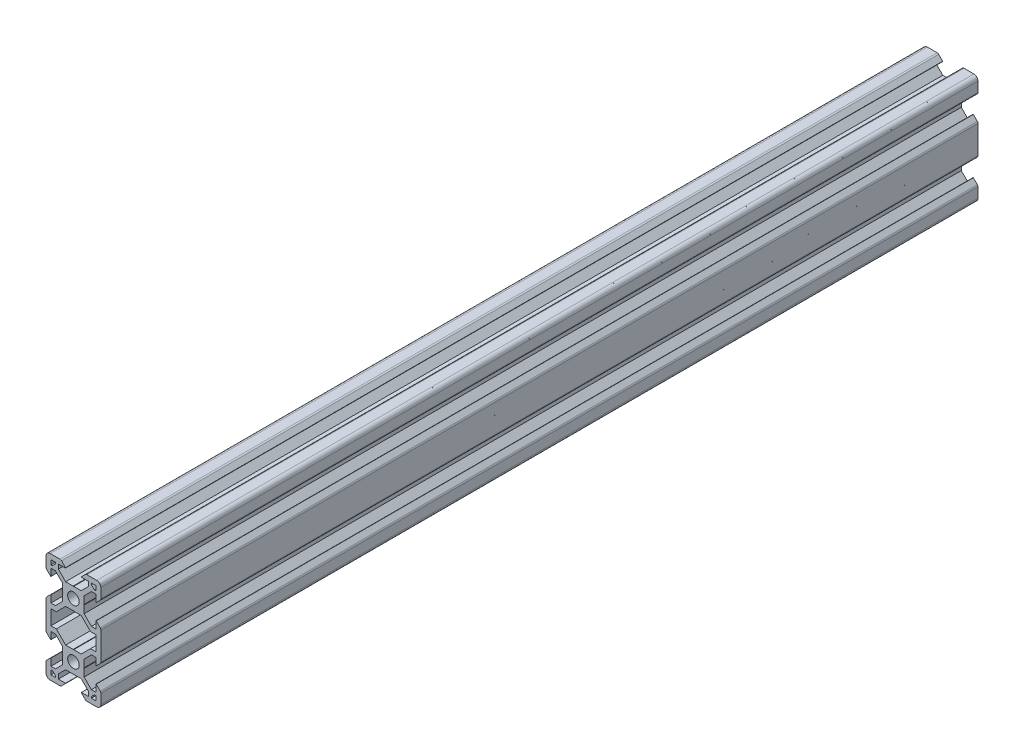
SolidWorks part; units mm, degrees
ref_plane "Front Plane" through (0, 0, 0) normal (0, 0, 1) x (1, 0, 0)
ref_plane "Top Plane" through (0, 0, 0) normal (0, 1, 0) x (1, 0, 0)
ref_plane "Right Plane" through (0, 0, 0) normal (1, 0, 0) x (0, 0, -1)
sketch "Sketch1" plane through (0, 0, 0) normal (0, 0, 1) x (1, 0, 0)
  line L0 (-8.2, 2.8875) -> (-8.2, 5.4975)
  line L3 (-4.9072, 9.9975) -> (-8.5, 9.9975)
  line L4 (-10, 4.9047) -> (-10, 8.4975)
  line L5 (-2.1, 0) -> (-3.8, 0) construction
  line L6 (0, 3.8) -> (0, 0) construction
  line L7 (-0.1, 3.9) -> (-2.8404, 3.9)
  line L8 (-3.9, 0.1) -> (-3.9, 2.8383)
  line L9 (-2.89, 8.1975) -> (-5.5, 8.1975)
  line L10 (-6.57, 8.1975) -> (-6.57, 7.6575)
  line L11 (-8.2, 6.5675) -> (-7.66, 6.5675)
  line L12 (-5.5, 8.1975) -> (-5.5, 6.5588)
  line L13 (-6.56, 5.4975) -> (-8.2, 5.4975)
  line L14 (-8.2, 8.1975) -> (-1.4852, 1.4847) construction
  line L15 (-6.56, 5.4975) -> (-3.9, 2.8383)
  line L16 (-5.5, 6.5588) -> (-2.8404, 3.9)
  line L17 (-7.66, 6.5675) -> (-6.57, 7.6575)
  line L18 (-8.7302, 7.6671) -> (-0.5302, -0.5304) construction
  line L19 (-7.6698, 8.7279) -> (0.5302, 0.5304) construction
  line L20 (-8.2, 8.1975) -> (0, 0) construction
  line L21 (-8.2, 6.5675) -> (-8.2, 8.1975)
  line L22 (-8.2, -0.0025) -> (-8.2, 8.1975) construction
  line L23 (-6.57, 8.1975) -> (-8.2, 8.1975)
  line L24 (0, 8.1975) -> (-8.2, 8.1975) construction
  line L25 (-10, -0.0025) -> (-10, 9.9975) construction
  line L26 (0, 9.9975) -> (-10, 9.9975) construction
  line L27 (-2.89, 8.3075) -> (-2.89, 8.1975)
  line L29 (-8.31, 2.8875) -> (-8.2, 2.8875)
  line L30 (-4.3486, 9.7661) -> (-2.89, 8.3075)
  line L31 (-8.31, 2.8875) -> (-9.7686, 4.3461)
  line L34 (-0.1, 3.9) -> (0, 3.8)
  line L35 (-3.9, 0.1) -> (-3.8, 0)
  line L36 (-8.2, -7.2996) -> (-6.24, -7.2996)
  line L37 (0, 0) -> (0, -10) construction
  line L38 (-0.1, -3.9) -> (-2.8404, -3.9)
  line L39 (-3.8, 0) -> (-3.9, -0.1)
  line L40 (-3.9, -0.1) -> (-3.9, -2.84)
  line L41 (-2.8404, -3.9) -> (-6.24, -7.2996)
  line L42 (-3.9, -2.84) -> (-6.56, -5.5)
  line L43 (-8.2, -2.89) -> (-8.2, -5.5)
  line L44 (-6.56, 5.4975) -> (-6.56, -5.5) construction
  line L45 (-6.56, -5.5) -> (-8.2, -5.5)
  line L46 (-0.1, -3.9) -> (0, -3.8)
  line L48 (-8.2, -2.89) -> (-8.31, -2.89)
  line L49 (-8.31, -2.89) -> (-9.7657, -4.3457)
  line L52 (-10, -10) -> (0, -10) construction
  line L53 (-8.2, -7.2996) -> (-8.2, -10)
  line L61 (-10, -4.9114) -> (-10, -10)
  arc A1 (-10, 8.4975) -> (-8.5, 9.9975) centre (-8.5, 8.4975) cw
  arc A2 (-9.7686, 4.3461) -> (-10, 4.9047) centre (-9.21, 4.9047) cw
  arc A3 (-4.3486, 9.7661) -> (-4.9072, 9.9975) centre (-4.9072, 9.2075) ccw
  arc A4 (-9.7657, -4.3457) -> (-10, -4.9114) centre (-9.2, -4.9114) ccw
  arc A6 (0, 2.1) -> (0, -2.1) centre (0, 0) ccw
  point P29 (-10, 9.9975)
  point P39 (-10, 4.5775)
  point P42 (-4.58, 9.9975)
  point P48 (-10, -4.58)
  dimension "D15" = 1.5
  dimension "D22" = 0.79
  dimension "D30" = 1.96
  dimension "D31" = 2.1
  dimension "D39" = 0.8
  dimension "D4" = 1.8
  dimension "D5" = 3.43
  dimension "D6" = 3.43
  dimension "D7" = 0.54
  dimension "D8" = 0.54
  dimension "D9" = 1.07
  dimension "D10" = 1.07
  dimension "D11" = 3.9
  dimension "D12" = 3.9
  dimension "D16" = 7.11
  dimension "D17" = 0.11
  dimension "D18" = 1.69
  dimension "D19" = 0.11
  dimension "D20" = 7.11
  dimension "D21" = 1.69
  dimension "D23" = 10
  dimension "D24" = 0.1
  dimension "D25" = 45
  dimension "D26" = 0.1
  dimension "D27" = 45
  dimension "D28" = 1.64
  dimension "D29" = 10
  dimension "D32" = 3.9
  dimension "D33" = 45
  dimension "D34" = 2.74
  dimension "D35" = 45
  dimension "D37" = 2.61
  dimension "D38" = 90
  dimension "D40" = 0.1
  dimension "D41" = 45
  dimension "D13" = 0.75
  dimension "D14" = 0.75
sketch "Sketch2" plane through (0, 0, 0) normal (0, 0, 1) x (1, 0, 0)
  line L0 (-0.1, 3.9) -> (0, 3.8) construction
  line L1 (-0.1, 3.9) -> (-2.8404, 3.9) construction
  line L2 (-5.5, 6.5588) -> (-2.8404, 3.9) construction
  line L3 (-5.5, 8.1975) -> (-5.5, 6.5588) construction
  line L4 (-2.89, 8.1975) -> (-5.5, 8.1975) construction
  line L5 (-7.66, 6.5675) -> (-6.57, 7.6575)
  line L6 (-6.57, 7.6575) -> (-6.57, 8.1975)
  line L7 (-6.57, 8.1975) -> (-8.2, 8.1975)
  line L8 (-8.2, 8.1975) -> (-8.2, 6.5675)
  line L9 (-8.2, 6.5675) -> (-7.66, 6.5675)
  line L10 (-7.66, 6.5675) -> (-6.57, 7.6575)
  line L11 (-6.57, 7.6575) -> (-6.57, 8.1975)
  line L12 (-6.57, 8.1975) -> (-8.2, 8.1975)
  line L13 (-8.2, 8.1975) -> (-8.2, 6.5675)
  line L14 (-8.2, 6.5675) -> (-7.66, 6.5675)
  line L15 (-2.89, 8.3075) -> (-2.89, 8.1975) construction
  line L16 (-4.3486, 9.7661) -> (-2.89, 8.3075) construction
  line L17 (-4.9072, 9.9975) -> (-8.5, 9.9975) construction
  line L18 (-10, 4.9047) -> (-10, 8.4975) construction
  line L19 (-8.31, 2.8875) -> (-9.7686, 4.3461) construction
  line L20 (-8.31, 2.8875) -> (-8.2, 2.8875) construction
  line L21 (-8.2, 2.8875) -> (-8.2, 5.4975) construction
  line L22 (-6.56, 5.4975) -> (-8.2, 5.4975) construction
  line L23 (-6.56, 5.4975) -> (-3.9, 2.8383) construction
  line L24 (-3.9, 0.1) -> (-3.9, 2.8383) construction
  line L25 (-3.9, 0.1) -> (-3.8, 0) construction
  line L26 (-3.8, 0) -> (-3.9, -0.1) construction
  line L27 (-3.9, -0.1) -> (-3.9, -2.84) construction
  line L28 (-3.9, -2.84) -> (-6.56, -5.5) construction
  line L29 (-6.56, -5.5) -> (-8.2, -5.5) construction
  line L30 (-8.2, -2.89) -> (-8.2, -5.5) construction
  line L31 (-8.2, -2.89) -> (-8.31, -2.89) construction
  line L32 (-8.31, -2.89) -> (-9.7657, -4.3457) construction
  line L33 (-10, -4.9114) -> (-10, -10) construction
  line L34 (-0.1, -3.9) -> (0, -3.8) construction
  line L35 (-0.1, -3.9) -> (-2.8404, -3.9) construction
  line L36 (-2.8404, -3.9) -> (-6.24, -7.2996) construction
  line L37 (-8.2, -7.2996) -> (-6.24, -7.2996) construction
  line L38 (-8.2, -7.2996) -> (-8.2, -10) construction
  line L39 (-0.1, 3.9) -> (0, 3.8)
  line L40 (-0.1, 3.9) -> (-2.8404, 3.9)
  line L41 (-5.5, 6.5588) -> (-2.8404, 3.9)
  line L42 (-5.5, 8.1975) -> (-5.5, 6.5588)
  line L43 (-2.89, 8.1975) -> (-5.5, 8.1975)
  line L44 (-2.89, 8.3075) -> (-2.89, 8.1975)
  line L45 (-4.3486, 9.7661) -> (-2.89, 8.3075)
  line L46 (-4.9072, 9.9975) -> (-8.5, 9.9975)
  line L47 (-10, 4.9047) -> (-10, 8.4975)
  line L48 (-8.31, 2.8875) -> (-9.7686, 4.3461)
  line L49 (-8.31, 2.8875) -> (-8.2, 2.8875)
  line L50 (-8.2, 2.8875) -> (-8.2, 5.4975)
  line L51 (-6.56, 5.4975) -> (-8.2, 5.4975)
  line L52 (-6.56, 5.4975) -> (-3.9, 2.8383)
  line L53 (-3.9, 0.1) -> (-3.9, 2.8383)
  line L54 (-3.9, 0.1) -> (-3.8, 0)
  line L55 (-3.8, 0) -> (-3.9, -0.1)
  line L56 (-3.9, -0.1) -> (-3.9, -2.84)
  line L57 (-3.9, -2.84) -> (-6.56, -5.5)
  line L58 (-6.56, -5.5) -> (-8.2, -5.5)
  line L59 (-8.2, -2.89) -> (-8.2, -5.5)
  line L60 (-8.2, -2.89) -> (-8.31, -2.89)
  line L61 (-8.31, -2.89) -> (-9.7657, -4.3457)
  line L62 (-10, -4.9114) -> (-10, -15.0886)
  line L63 (-0.1, -3.9) -> (0, -3.8)
  line L64 (-0.1, -3.9) -> (-2.8404, -3.9)
  line L65 (-2.8404, -3.9) -> (-6.24, -7.2996)
  line L66 (-8.2, -7.2996) -> (-6.24, -7.2996)
  line L67 (-8.2, -7.2996) -> (-8.2, -12.7004)
  line L68 (0, 0) -> (0, -10) construction
  line L69 (-10, -10) -> (0, -10) construction
  line L70 (0, 0) -> (0, -20) construction
  line L71 (-10, -10) -> (10, -10) construction
  line L72 (8.2, -7.2996) -> (8.2, -12.7004)
  line L73 (8.2, -7.2996) -> (6.24, -7.2996)
  line L74 (2.8404, -3.9) -> (6.24, -7.2996)
  line L75 (0.1, -3.9) -> (2.8404, -3.9)
  line L76 (0.1, -3.9) -> (0, -3.8)
  line L77 (10, -4.9114) -> (10, -15.0886)
  line L78 (8.31, -2.89) -> (9.7657, -4.3457)
  line L79 (8.2, -2.89) -> (8.31, -2.89)
  line L80 (8.2, -2.89) -> (8.2, -5.5)
  line L81 (6.56, -5.5) -> (8.2, -5.5)
  line L82 (3.9, -2.84) -> (6.56, -5.5)
  line L83 (3.9, -0.1) -> (3.9, -2.84)
  line L84 (3.8, 0) -> (3.9, -0.1)
  line L85 (3.9, 0.1) -> (3.8, 0)
  line L86 (3.9, 0.1) -> (3.9, 2.8383)
  line L87 (6.56, 5.4975) -> (3.9, 2.8383)
  line L88 (6.56, 5.4975) -> (8.2, 5.4975)
  line L89 (8.2, 2.8875) -> (8.2, 5.4975)
  line L90 (8.31, 2.8875) -> (8.2, 2.8875)
  line L91 (8.31, 2.8875) -> (9.7686, 4.3461)
  line L92 (10, 4.9047) -> (10, 8.4975)
  line L93 (4.9072, 9.9975) -> (8.5, 9.9975)
  line L94 (4.3486, 9.7661) -> (2.89, 8.3075)
  line L95 (2.89, 8.3075) -> (2.89, 8.1975)
  line L96 (2.89, 8.1975) -> (5.5, 8.1975)
  line L97 (5.5, 8.1975) -> (5.5, 6.5588)
  line L98 (5.5, 6.5588) -> (2.8404, 3.9)
  line L99 (0.1, 3.9) -> (2.8404, 3.9)
  line L100 (0.1, 3.9) -> (0, 3.8)
  line L101 (8.2, 6.5675) -> (7.66, 6.5675)
  line L102 (8.2, 8.1975) -> (8.2, 6.5675)
  line L103 (6.57, 8.1975) -> (8.2, 8.1975)
  line L104 (6.57, 7.6575) -> (6.57, 8.1975)
  line L105 (7.66, 6.5675) -> (6.57, 7.6575)
  line L106 (7.66, -26.5675) -> (6.57, -27.6575)
  line L107 (6.57, -27.6575) -> (6.57, -28.1975)
  line L108 (6.57, -28.1975) -> (8.2, -28.1975)
  line L109 (8.2, -28.1975) -> (8.2, -26.5675)
  line L110 (8.2, -26.5675) -> (7.66, -26.5675)
  line L111 (0.1, -23.9) -> (0, -23.8)
  line L112 (0.1, -23.9) -> (2.8404, -23.9)
  line L113 (5.5, -26.5588) -> (2.8404, -23.9)
  line L114 (5.5, -28.1975) -> (5.5, -26.5588)
  line L115 (2.89, -28.1975) -> (5.5, -28.1975)
  line L116 (2.89, -28.3075) -> (2.89, -28.1975)
  line L117 (4.3486, -29.7661) -> (2.89, -28.3075)
  line L118 (4.9072, -29.9975) -> (8.5, -29.9975)
  line L119 (10, -24.9047) -> (10, -28.4975)
  line L120 (8.31, -22.8875) -> (9.7686, -24.3461)
  line L121 (8.31, -22.8875) -> (8.2, -22.8875)
  line L122 (8.2, -22.8875) -> (8.2, -25.4975)
  line L123 (6.56, -25.4975) -> (8.2, -25.4975)
  line L124 (6.56, -25.4975) -> (3.9, -22.8383)
  line L125 (3.9, -20.1) -> (3.9, -22.8383)
  line L126 (3.9, -20.1) -> (3.8, -20)
  line L127 (3.8, -20) -> (3.9, -19.9)
  line L128 (3.9, -19.9) -> (3.9, -17.16)
  line L129 (3.9, -17.16) -> (6.56, -14.5)
  line L130 (6.56, -14.5) -> (8.2, -14.5)
  line L131 (8.2, -17.11) -> (8.2, -14.5)
  line L132 (8.2, -17.11) -> (8.31, -17.11)
  line L133 (8.31, -17.11) -> (9.7657, -15.6543)
  line L134 (0.1, -16.1) -> (0, -16.2)
  line L135 (0.1, -16.1) -> (2.8404, -16.1)
  line L136 (2.8404, -16.1) -> (6.24, -12.7004)
  line L137 (8.2, -12.7004) -> (6.24, -12.7004)
  line L138 (-8.2, -12.7004) -> (-6.24, -12.7004)
  line L139 (-2.8404, -16.1) -> (-6.24, -12.7004)
  line L140 (-0.1, -16.1) -> (-2.8404, -16.1)
  line L141 (-0.1, -16.1) -> (0, -16.2)
  line L142 (-8.31, -17.11) -> (-9.7657, -15.6543)
  line L143 (-8.2, -17.11) -> (-8.31, -17.11)
  line L144 (-8.2, -17.11) -> (-8.2, -14.5)
  line L145 (-6.56, -14.5) -> (-8.2, -14.5)
  line L146 (-3.9, -17.16) -> (-6.56, -14.5)
  line L147 (-3.9, -19.9) -> (-3.9, -17.16)
  line L148 (-3.8, -20) -> (-3.9, -19.9)
  line L149 (-3.9, -20.1) -> (-3.8, -20)
  line L150 (-3.9, -20.1) -> (-3.9, -22.8383)
  line L151 (-6.56, -25.4975) -> (-3.9, -22.8383)
  line L152 (-6.56, -25.4975) -> (-8.2, -25.4975)
  line L153 (-8.2, -22.8875) -> (-8.2, -25.4975)
  line L154 (-8.31, -22.8875) -> (-8.2, -22.8875)
  line L155 (-8.31, -22.8875) -> (-9.7686, -24.3461)
  line L156 (-10, -24.9047) -> (-10, -28.4975)
  line L157 (-4.9072, -29.9975) -> (-8.5, -29.9975)
  line L158 (-4.3486, -29.7661) -> (-2.89, -28.3075)
  line L159 (-2.89, -28.3075) -> (-2.89, -28.1975)
  line L160 (-2.89, -28.1975) -> (-5.5, -28.1975)
  line L161 (-5.5, -28.1975) -> (-5.5, -26.5588)
  line L162 (-5.5, -26.5588) -> (-2.8404, -23.9)
  line L163 (-0.1, -23.9) -> (-2.8404, -23.9)
  line L164 (-0.1, -23.9) -> (0, -23.8)
  line L165 (-8.2, -26.5675) -> (-7.66, -26.5675)
  line L166 (-8.2, -28.1975) -> (-8.2, -26.5675)
  line L167 (-6.57, -28.1975) -> (-8.2, -28.1975)
  line L168 (-6.57, -27.6575) -> (-6.57, -28.1975)
  line L169 (-7.66, -26.5675) -> (-6.57, -27.6575)
  arc A0 (0, 2.1) -> (0, -2.1) centre (0, 0) ccw construction
  arc A1 (-4.3486, 9.7661) -> (-4.9072, 9.9975) centre (-4.9072, 9.2075) ccw construction
  arc A2 (-8.5, 9.9975) -> (-10, 8.4975) centre (-8.5, 8.4975) ccw construction
  arc A3 (-10, 4.9047) -> (-9.7686, 4.3461) centre (-9.21, 4.9047) ccw construction
  arc A4 (-9.7657, -4.3457) -> (-10, -4.9114) centre (-9.2, -4.9114) ccw construction
  circle A5 centre (0, 0) radius 2.1
  arc A6 (-4.3486, 9.7661) -> (-4.9072, 9.9975) centre (-4.9072, 9.2075) ccw
  arc A7 (-8.5, 9.9975) -> (-10, 8.4975) centre (-8.5, 8.4975) ccw
  arc A8 (-10, 4.9047) -> (-9.7686, 4.3461) centre (-9.21, 4.9047) ccw
  arc A9 (-9.7657, -4.3457) -> (-10, -4.9114) centre (-9.2, -4.9114) ccw
  arc A10 (9.7657, -4.3457) -> (10, -4.9114) centre (9.2, -4.9114) cw
  arc A11 (10, 4.9047) -> (9.7686, 4.3461) centre (9.21, 4.9047) cw
  arc A12 (8.5, 9.9975) -> (10, 8.4975) centre (8.5, 8.4975) cw
  arc A13 (4.3486, 9.7661) -> (4.9072, 9.9975) centre (4.9072, 9.2075) cw
  arc A14 (4.3486, -29.7661) -> (4.9072, -29.9975) centre (4.9072, -29.2075) ccw
  arc A15 (8.5, -29.9975) -> (10, -28.4975) centre (8.5, -28.4975) ccw
  arc A16 (10, -24.9047) -> (9.7686, -24.3461) centre (9.21, -24.9047) ccw
  arc A17 (9.7657, -15.6543) -> (10, -15.0886) centre (9.2, -15.0886) ccw
  arc A18 (-9.7657, -15.6543) -> (-10, -15.0886) centre (-9.2, -15.0886) cw
  arc A19 (-10, -24.9047) -> (-9.7686, -24.3461) centre (-9.21, -24.9047) cw
  arc A20 (-8.5, -29.9975) -> (-10, -28.4975) centre (-8.5, -28.4975) cw
  arc A21 (-4.3486, -29.7661) -> (-4.9072, -29.9975) centre (-4.9072, -29.2075) cw
  circle A22 centre (0, -20) radius 2.1
  point P147 (8.2, -10)
  dimension "D1" = 0
extrude "Boss-Extrude1" add sketch "Sketch2" against normal blind 320
